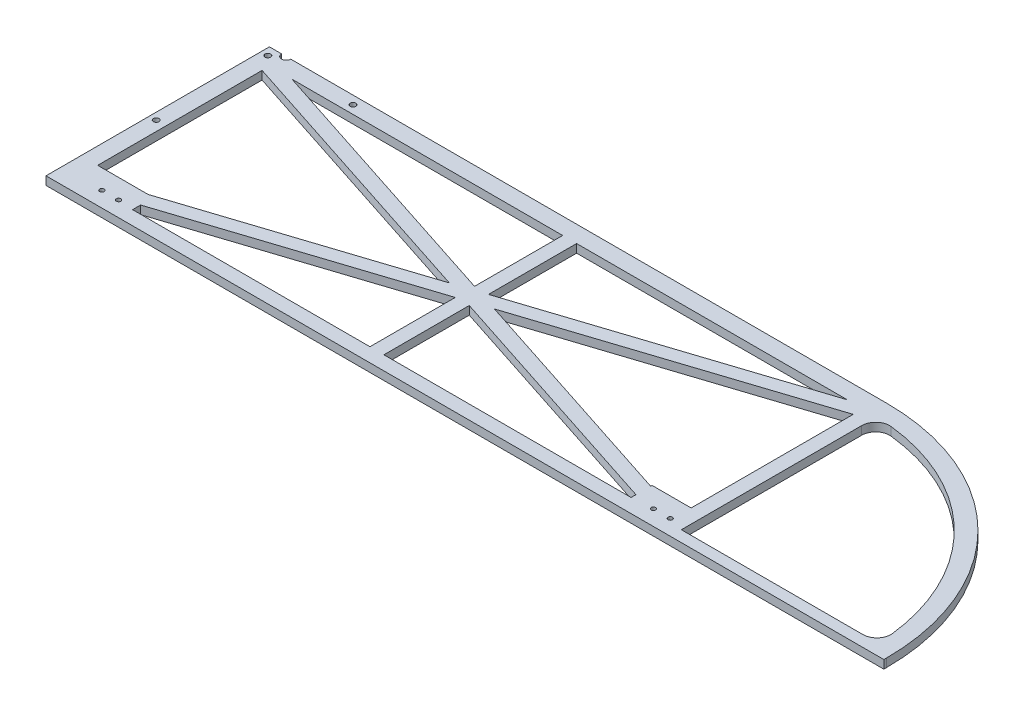
SolidWorks part; units mm, degrees
material "轻木"
ref_plane "前视基准面" through (0, 0, 0) normal (0, 0, 1) x (1, 0, 0)
ref_plane "上视基准面" through (0, 0, 0) normal (0, 1, 0) x (1, 0, 0)
ref_plane "右视基准面" through (0, 0, 0) normal (1, 0, 0) x (0, 0, -1)
other "Configuration Table"
sketch "草图1" plane through (0, 0, 0) normal (0, 1, 0) x (1, 0, 0)
  line L31 (-111.0578, 34) -> (-111.0578, 40) construction
  line L32 (-150, 40) -> (71, 40)
  line L37 (-150, 40) -> (-150, -40)
  line L60 (-150, -40) -> (150, -40)
  line L62 (150, -39) -> (150, -40)
  line L64 (-150, 40) -> (150, -40) construction
  line L72 (-150, -40) -> (150, 40) construction
  line L73 (-117.0578, 37) -> (-147.5578, 37) construction
  line L74 (-147.5578, 37) -> (-147.5578, -3) construction
  line L75 (-144.5578, -10) -> (-144.5578, 34) construction
  arc A5 (71, 40) -> (150, -39) centre (71, -39) cw
  circle A6 centre (-117.0578, 37) radius 1
  circle A7 centre (-147.5578, 37) radius 1
  circle A8 centre (-147.5578, -3) radius 1
  point P0 (0, 0)
  point P13 (-111.0578, 37)
  dimension "D3" = 79
  dimension "D4" = 2
  dimension "D1" = 80
  dimension "D2" = 300
  dimension "D9" = 3
  dimension "D5" = 6
  dimension "D6" = 40
  dimension "D7" = 2
  dimension "D8" = 2
extrude "凸台-拉伸1" add sketch "草图1" along normal blind 3
sketch "草图4" plane through (0, 0, 0) normal (0, 1, 0) x (1, 0, 0)
  line L4 (71, 34) -> (-144, 34)
  line L9 (-144, 34) -> (-144, -36)
  line L10 (71, 34) -> (71, -36) construction
  line L11 (71, 36) -> (-146, 36)
  line L12 (-146, 36) -> (-146, -36)
  line L13 (-146, -36) -> (145.94, -36)
  line L14 (71, 36) -> (-146, 36) construction
  line L15 (-146, 36) -> (-146, -36) construction
  line L16 (-144, -36) -> (138.5278, -36)
  line L17 (-144, 34) -> (71, -36) construction
  line L19 (71, 34) -> (-144, -36) construction
  line L21 (-36.5, -36) -> (-36.5, 34) construction
  line L22 (-34, -36) -> (-34, 34)
  line L23 (-144, 31.3708) -> (62.9247, -36)
  line L24 (73.5, 28.5851) -> (73.5, -36)
  line L25 (62.9247, 34) -> (-144, -33.3708)
  line L26 (-39, -36) -> (-39, 34)
  line L27 (-135.9247, 34) -> (68.5, -32.5569)
  line L28 (68.5, 34) -> (68.5, -32.5569)
  line L29 (71.774, 31.6228) -> (71, 31.3708)
  line L30 (-144.774, 31.6228) -> (73.5, -39.4431) construction
  line L31 (73.5, 34) -> (73.5, -39.4431) construction
  line L32 (70.226, 36.3772) -> (-144.774, -33.6228) construction
  line L33 (68.5, 30.5569) -> (-135.9247, -36)
  line L34 (71.774, 31.6228) -> (-143.226, -38.3772) construction
  line L35 (-143.226, 36.3772) -> (68.5, -32.5569) construction
  line L36 (-136.5, -33.5) -> (-134.5, -33.5) construction
  line L37 (68.5, -36) -> (54.5, -36)
  line L38 (68.5, -36) -> (68.5, -27.5)
  line L39 (68.5, -27.5) -> (54.5, -27.5)
  line L40 (54.5, -36) -> (54.5, -27.5)
  line L41 (-144, -36) -> (-124, -36)
  line L42 (-144, -36) -> (-144, -27.5)
  line L43 (-144, -27.5) -> (-124, -27.5)
  line L44 (-124, -36) -> (-124, -27.5)
  line L49 (-136.5, -33.5) -> (-136.5, -49.5) construction
  line L50 (-135.5, -34.5) -> (-129.5, -34.5) construction
  line L51 (-135.5, -34.5) -> (62, -34.5) construction
  line L52 (-150, 40) -> (71, 40) construction
  arc A3 (145.94, -36) -> (71, 36) centre (71, -39) ccw
  arc A4 (145.94, -36) -> (71, 36) centre (71, -39) ccw construction
  arc A5 (143.493, -30.4118) -> (79.0515, 33.5546) centre (71, -39) ccw
  arc A6 (143.9416, -36.08) -> (71, 34) centre (71, -39) ccw construction
  arc A7 (138.5278, -36) -> (143.493, -30.4118) centre (138.5278, -31) ccw
  arc A8 (73.5, 28.5851) -> (79.0515, 33.5546) centre (78.5, 28.5851) cw
  circle A10 centre (-135.5, -34.5) radius 0.8
  circle A11 centre (-129.5, -34.5) radius 0.8
  circle A12 centre (62, -34.5) radius 0.8
  circle A13 centre (68, -34.5) radius 0.8
  circle A14 centre (-144, 40) radius 1.65
  point P69 (0, 0)
  dimension "D18" = 3.3
  dimension "D9" = 5
  dimension "D10" = 5
  dimension "D14" = 1.6
  dimension "D2" = 2
  dimension "D3" = 2.5
  dimension "D5" = 8.5
  dimension "D7" = 20
  dimension "D11" = 90
  dimension "D12" = 1
  dimension "D13" = 1
  dimension "D15" = 2
  dimension "D16" = 6
  dimension "D17" = 197.5
  dimension "D8" = 8.5
  dimension "D6" = 14
  dimension "D1" = 4
  dimension "D4" = 2.5
extrude "切除-拉伸2" cut sketch "草图4" along normal blind 18
sketch "草图6" plane through (0, 3, 0) normal (0, 1, 0) x (1, 0, 0)
  line L0 (54.5, -33.2571) -> (54.5, -36) construction
  line L1 (-124, -36) -> (54.5, -36)
  line L2 (-124, -36) -> (-124, -35)
  line L3 (-124, -35) -> (54.5, -35)
  line L4 (54.5, -36) -> (54.5, -35)
  dimension "D1" = 1
extrude "凸台-拉伸2" add sketch "草图6" against normal through all
